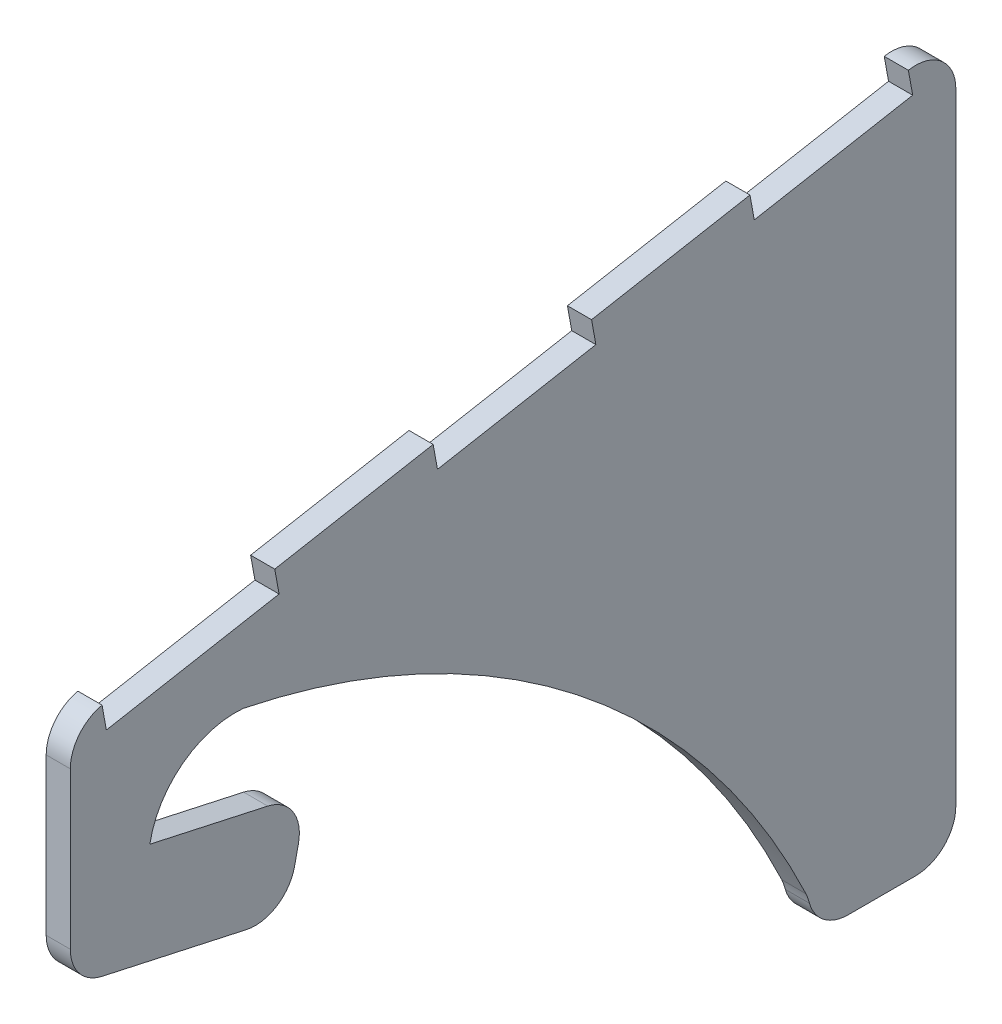
SolidWorks part; units mm, degrees
ref_plane "Front Plane" through (0, 0, 0) normal (0, 0, 1) x (1, 0, 0)
ref_plane "Top Plane" through (0, 0, 0) normal (0, 1, 0) x (1, 0, 0)
ref_plane "Right Plane" through (0, 0, 0) normal (1, 0, 0) x (0, 0, -1)
sketch "Sketch1" plane through (0, 0, 0) normal (1, 0, 0) x (0, 0, -1)
  line L1 (0, 0) -> (110, 0)
  line L2 (0, 0) -> (0, -110)
  line L3 (0, -110) -> (110, -110)
  line L4 (110, 0) -> (110, -110)
  dimension "D1" = 110
  dimension "D2" = 110
extrude "Boss-Extrude1" add sketch "Sketch1" along normal blind 3
sketch "Sketch2" plane through (3, 0, 0) normal (1, 0, 0) x (0, 0, -1)
  line L0 (26.7788, -55.8815) -> (29.4098, -43.907)
  line L1 (24.1478, -67.856) -> (29.4098, -43.907) construction
  line L2 (29.4098, -43.907) -> (9.8758, -39.615)
  line L3 (90.7443, -95.3255) -> (80.8646, -107.8202)
  line L4 (80.8646, -107.8202) -> (79.449, -110)
  line L5 (0, -110) -> (110, -110) construction
  line L6 (2.3349, -228.7453) -> (80.8646, -107.8202) construction
  line L7 (79.449, -110) -> (0, -110)
  line L8 (0, -110) -> (0, -69.7276)
  line L9 (0, 0) -> (0, -110) construction
  line L10 (3.1436, -66.3576) -> (-166.335, -248.0425) construction
  line L11 (0, -69.7276) -> (3.1436, -66.3576)
  line L12 (4.6138, -63.5641) -> (24.1478, -67.856)
  line L13 (24.1478, -67.856) -> (26.7788, -55.8815)
  arc A0 (9.8758, -39.615) -> (21.5001, -30.8059) centre (20.4961, -41.5551) cw
  arc A1 (21.5001, -30.8059) -> (91.385, -85.696) centre (1.3202, -128.4314) cw
  arc A2 (91.385, -85.696) -> (90.7443, -95.3255) centre (81.4207, -89.8691) cw
  arc A3 (3.1436, -66.3576) -> (4.6138, -63.5641) centre (0.1282, -62.987) ccw
  dimension "D1" = 10.796
  dimension "D2" = 99.6894
  dimension "D3" = 10.8028
  dimension "D4" = 4.5226
extrude "Cut-Extrude1" cut sketch "Sketch2" against normal blind 10
sketch "Sketch3" plane through (3, 0, 0) normal (1, 0, 0) x (0, 0, -1)
  line L0 (26.7788, -55.8815) -> (0, -49.9977)
  line L1 (29.4098, -43.907) -> (24.1478, -67.856) construction
  line L2 (0, 0) -> (0, -69.7276) construction
  line L3 (0, -49.9977) -> (0, -22.3927)
  line L4 (0, -22.3927) -> (110, -2.3927)
  line L5 (110, -110) -> (110, 0) construction
  line L6 (110, -2.3927) -> (110, 0)
  line L7 (110, 0) -> (0, 0)
  line L8 (0, 0) -> (-15.4465, -25.1683)
  line L10 (-15.4465, -25.1683) -> (-7.2392, -70.3086)
  line L11 (-7.2392, -70.3086) -> (0, -69.7276)
  line L12 (0, -69.7276) -> (28.6623, -73.689)
  line L13 (28.6623, -73.689) -> (31.1234, -55.8815)
  line L14 (31.1234, -55.8815) -> (26.7788, -55.8815)
  dimension "D1" = 20
extrude "Cut-Extrude2" cut sketch "Sketch3" against normal blind 10
sketch "Sketch4" plane through (3, 0, 0) normal (1, 0, 0) x (0, 0, -1)
  line L0 (92.1997, -90.5863) -> (110, -90.5863)
  line L1 (110, -110) -> (110, -2.3927) construction
  line L2 (110, -90.5863) -> (115.8497, -112.5772)
  line L3 (115.8497, -112.5772) -> (92.1997, -118.8682)
  line L4 (92.1997, -118.8682) -> (68.11, -115.7227)
  line L5 (68.11, -115.7227) -> (77.6206, -97.2502)
  line L6 (77.6206, -97.2502) -> (92.1997, -90.5863)
  arc A0 (90.7443, -95.3255) -> (91.385, -85.696) centre (81.4207, -89.8691) ccw construction
extrude "Cut-Extrude3" cut sketch "Sketch4" against normal blind 10
fillet "Fillet1" radius 5 7 edges at (1.5, -43.907, -29.4098) (1.5, -55.8815, -26.7788) (1.5, -2.3927, -110) (1.5, -90.5863, -92.1997) (1.5, -90.5863, -110) (1.5, -22.3927, 0) (1.5, -49.9977, 0)
sketch "Sketch5" plane through (0, -21.6761, -3.9411) normal (0, 0.9839, 0.1789) x (1, 0, 0)
  line L16 (0, 101.8066) -> (3, 101.8066)
  line L17 (0, 101.8066) -> (0, 81.8066)
  line L18 (0, 81.8066) -> (3, 81.8066)
  line L19 (3, 101.8066) -> (3, 81.8066)
  line L20 (0, 61.8066) -> (3, 61.8066)
  line L21 (0, 61.8066) -> (0, 41.8066)
  line L22 (0, 41.8066) -> (3, 41.8066)
  line L23 (3, 61.8066) -> (3, 41.8066)
  line L26 (0, 0) -> (3, 0)
  line L27 (0, 0) -> (0, 21.8066)
  line L28 (0, 21.8066) -> (3, 21.8066)
  line L29 (3, 0) -> (3, 21.8066)
  point P23 (1.5, 21.8066)
  dimension "D1" = 20
  dimension "D2" = 20
  dimension "D3" = 20
  dimension "D4" = 20
  dimension "D5" = 21.8066
extrude "Cut-Extrude4" cut sketch "Sketch5" against normal blind 3
